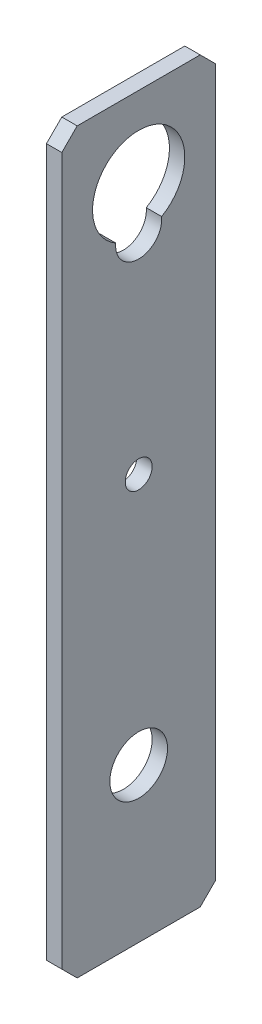
SolidWorks part; units mm, degrees
ref_plane "Front Plane" through (0, 0, 0) normal (0, 0, 1) x (1, 0, 0)
ref_plane "Top Plane" through (0, 0, 0) normal (0, 1, 0) x (1, 0, 0)
ref_plane "Right Plane" through (0, 0, 0) normal (1, 0, 0) x (0, 0, -1)
sketch "Sketch1" plane through (0, 0, 0) normal (1, 0, 0) x (0, 0, -1)
  line L1 (-10, -48) -> (10, -48)
  line L2 (-10, -48) -> (-10, 48)
  line L3 (-10, 48) -> (10, 48)
  line L4 (10, -48) -> (10, 48)
  line L5 (-10, -48) -> (10, 48) construction
  line L6 (-10, 48) -> (10, -48) construction
  point P0 (0, 0)
  dimension "D1" = 96
  dimension "D2" = 20
extrude "Boss-Extrude2" add sketch "Sketch1" along normal blind 2
sketch "Sketch3" plane through (2, 0, 0) normal (1, 0, 0) x (0, 0, -1)
  line L0 (-10, -48) -> (10, -48) construction
  line L1 (10, 48) -> (-10, 48) construction
  circle A0 centre (0, 4.75) radius 1.75
  arc A1 (2.9854, 32.2955) -> (-2.9854, 32.2955) centre (0, 37.5) ccw
  circle A2 centre (0, -28) radius 3.75
  arc A3 (-2.9854, 32.2955) -> (2.9854, 32.2955) centre (0, 32) ccw
  dimension "D1" = 7.5
  dimension "D2" = 3.5
  dimension "D3" = 12
  dimension "D4" = 32.75
  dimension "D7" = 5.5
  dimension "D8" = 6
  dimension "D5" = 20
  dimension "D6" = 10.5
extrude "Cut-Extrude1" cut sketch "Sketch3" against normal through all
chamfer "Chamfer1" distance 2 angle 45 4 edges at (1, -48, 10) (1, -48, -10) (1, 48, -10) (1, 48, 10)
